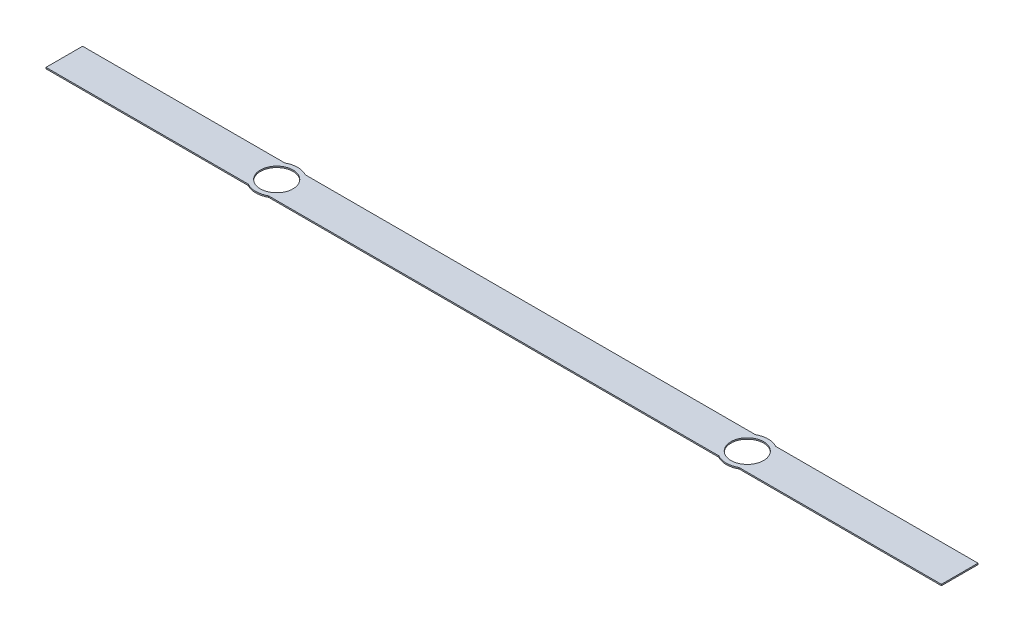
SolidWorks part; units mm, degrees
ref_plane "Front Plane" through (0, 0, 0) normal (0, 0, 1) x (1, 0, 0)
ref_plane "Top Plane" through (0, 0, 0) normal (0, 1, 0) x (1, 0, 0)
ref_plane "Right Plane" through (0, 0, 0) normal (1, 0, 0) x (0, 0, -1)
sketch "Sketch1" plane through (0, 0, 0) normal (0, 1, 0) x (1, 0, 0)
  line L0 (-53.7465, 0) -> (53.7465, 0) construction
  line L1 (-34.25, 1.4) -> (-18.7746, 1.4)
  line L2 (-34.25, 1.4) -> (-34.25, -1.4)
  line L3 (-34.25, -1.4) -> (-18.7746, -1.4)
  line L4 (34.25, 1.4) -> (34.25, -1.4)
  line L5 (0, 28.9014) -> (0, -25.6338) construction
  line L6 (-17.2254, -1.4) -> (17.2254, -1.4)
  line L7 (-17.2254, 1.4) -> (17.2254, 1.4)
  line L8 (18.7746, -1.4) -> (34.25, -1.4)
  line L9 (18.7746, 1.4) -> (34.25, 1.4)
  circle A0 centre (-18, 0) radius 1.25
  circle A1 centre (18, 0) radius 1.25
  arc A2 (-17.2254, 1.4) -> (-18.7746, 1.4) centre (-18, 0) ccw
  arc A3 (-18.7746, -1.4) -> (-17.2254, -1.4) centre (-18, 0) ccw
  arc A4 (18.7746, -1.4) -> (17.2254, -1.4) centre (18, 0) cw
  arc A5 (17.2254, 1.4) -> (18.7746, 1.4) centre (18, 0) cw
  dimension "D3" = 2.5
  dimension "D4" = 36
  dimension "D5" = 3.2
  dimension "D1" = 2.8
  dimension "D2" = 68.5
extrude "Boss-Extrude1" add sketch "Sketch1" along normal blind 0.1
